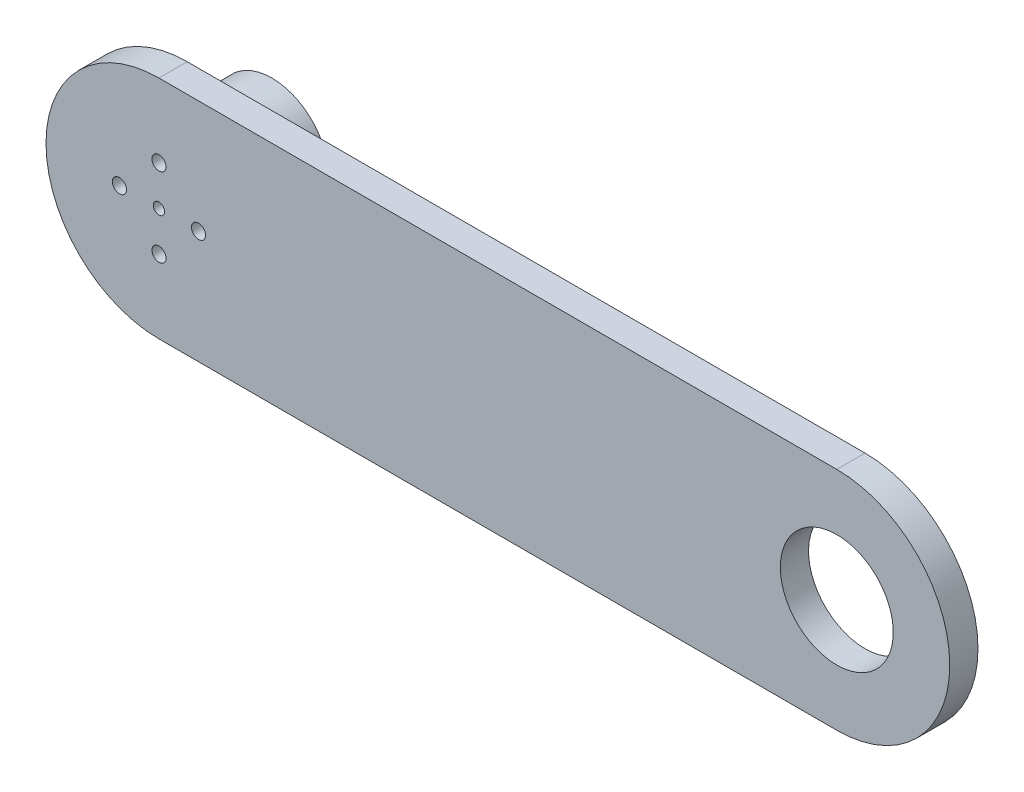
SolidWorks part; units mm, degrees
ref_plane "Front Plane" through (0, 0, 0) normal (0, 0, 1) x (1, 0, 0)
ref_plane "Top Plane" through (0, 0, 0) normal (0, 1, 0) x (1, 0, 0)
ref_plane "Right Plane" through (0, 0, 0) normal (1, 0, 0) x (0, 0, -1)
sketch "Sketch1" plane through (0, 0, 0) normal (0, 1, 0) x (1, 0, 0)
  line L0 (120, -20) -> (0, -20)
  line L2 (0, 20) -> (120, 20)
  arc A0 (0, 20) -> (0, -20) centre (0, 0) ccw
  arc A1 (120, -20) -> (120, 20) centre (120, 0) ccw
  dimension "D1" = 40
  dimension "D3" = 120
  dimension "D2" = 2
extrude "Boss-Extrude1" add sketch "Sketch1" along normal blind 5 contours L2 A1 L0 A0
sketch "Sketch2" plane through (0, 5, 0) normal (0, 1, 0) x (1, 0, 0)
  circle A0 centre (0, 0) radius 1
  circle A1 centre (0, 7) radius 1.25
  circle A2 centre (0.001, 0.001) radius 1
  circle A3 centre (7.001, 0.001) radius 1.25
  circle A4 centre (0.002, 0) radius 1
  circle A5 centre (0.002, -7) radius 1.25
  circle A6 centre (0.001, -0.001) radius 1
  circle A7 centre (-6.999, -0.001) radius 1.25
  point P20 (0.001, 0)
  dimension "D1" = 2
  dimension "D2" = 2.5
  dimension "D4" = 7
  dimension "D3" = 4
extrude "Cut-Extrude1" cut sketch "Sketch2" against normal up to next contours A1 | A0 | A3 | A5 | A7
sketch "Sketch3" plane through (0, 5, 0) normal (0, 1, 0) x (1, 0, 0)
  line L0 (120, 0) -> (140, 0) construction
  arc A0 (120, -20) -> (120, 20) centre (120, 0) ccw construction
  circle A6 centre (120, 0) radius 10
  dimension "D1" = 20
  dimension "D2" = 20
extrude "Cut-Extrude2" cut sketch "Sketch3" against normal up to next
move or copy body "Body-Move/Copy1" bodies to move or copy 104 copy no rotation origin (0, 0, 0) rotation axis (1, 0, 0) rotation angle 90
sketch "Sketch12" plane through (0, 0, 0) normal (0, 0, -1) x (-1, 0, 0)
  circle A0 centre (0, 0) radius 10
  dimension "D1" = 20
extrude "Boss-Extrude2" add sketch "Sketch12" along normal blind 15
move or copy body "Body-Move/Copy4" bodies to move or copy 110 copy no translate (0, 0, -5)
